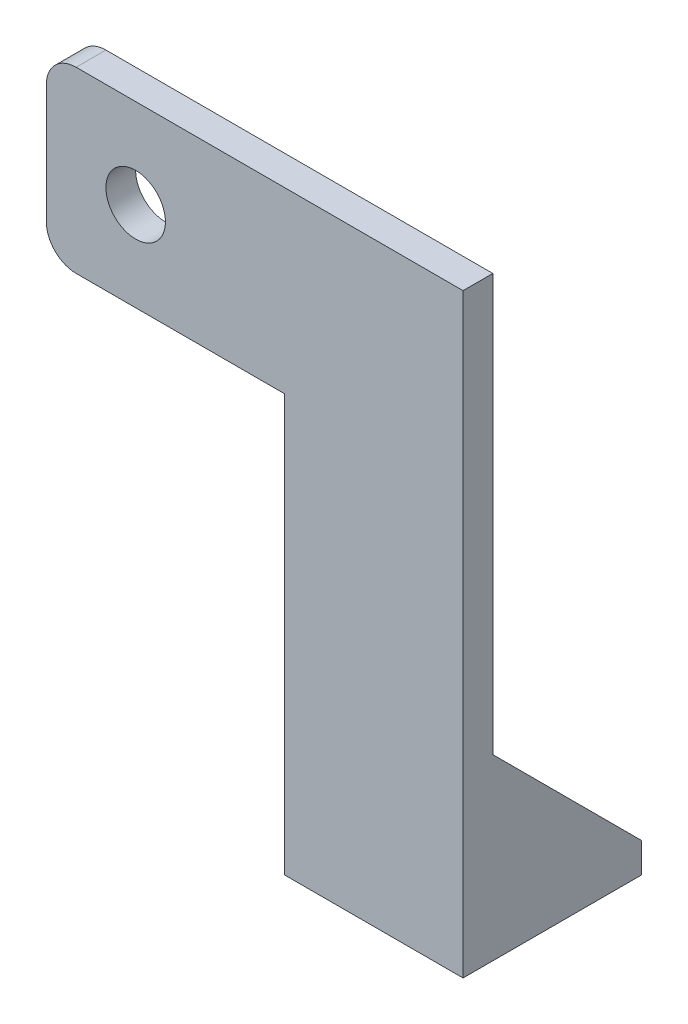
SolidWorks part; units mm, degrees
ref_plane "Front Plane" through (0, 0, 0) normal (0, 0, 1) x (1, 0, 0)
ref_plane "Top Plane" through (0, 0, 0) normal (0, 1, 0) x (1, 0, 0)
ref_plane "Right Plane" through (0, 0, 0) normal (1, 0, 0) x (0, 0, -1)
sketch "Sketch1" plane through (0, 0, 0) normal (0, 0, 1) x (1, 0, 0)
  line L0 (0, -15) -> (6.6093, -15) construction
  line L1 (5, 0) -> (70, 0)
  line L2 (0, -5) -> (0, -25)
  line L3 (5, -30) -> (40, -30)
  line L4 (70, 0) -> (70, -30)
  line L6 (70, -30) -> (70, -95)
  line L7 (70, -95) -> (40, -95)
  line L8 (40, -30) -> (40, -95)
  arc A1 (5, 0) -> (0, -5) centre (5, -5) ccw
  arc A2 (5, -30) -> (0, -25) centre (5, -25) cw
  dimension "D5" = 10
  dimension "D1" = 30
  dimension "D2" = 70
  dimension "D3" = 30
  dimension "D4" = 65
extrude "Boss-Extrude1" add sketch "Sketch1" along normal blind 5 contours L1 L4 L6 L7 L8 L3 A2 L2 A1
ref_plane "Plane1" through (55, 0, 0) normal (-1, 0, 0) x (0, 0, 1)
sketch "Sketch4" plane through (0, 0, 5) normal (0, 0, 1) x (1, 0, 0)
  line L0 (0, -5) -> (0, -25) construction
  line L1 (5, 0) -> (70, 0) construction
  circle A0 centre (15, -15) radius 5
  dimension "D1" = 10
  dimension "D2" = 15
  dimension "D3" = 15
extrude "Cut-Extrude1" cut sketch "Sketch4" against normal blind 5 contours A0
sketch "Sketch5" plane through (0, -95, 0) normal (0, -1, 0) x (1, 0, 0)
  line L0 (70, 5) -> (70, 0) construction
  line L1 (40, 5) -> (70, 5)
  line L2 (40, 5) -> (40, -25)
  line L3 (40, -25) -> (70, -25)
  line L4 (70, 5) -> (70, -25)
  dimension "D1" = 30
extrude "Boss-Extrude4" add sketch "Sketch5" along normal blind 5
sketch "Sketch6" plane through (70, 0, 0) normal (1, 0, 0) x (0, 0, -1)
  line L0 (0, -70) -> (25, -95)
  line L1 (0, 0) -> (0, -95) construction
  line L2 (0, -70) -> (0, -95)
  line L3 (0, -95) -> (25, -95)
extrude "Boss-Extrude5" add sketch "Sketch6" against normal blind 5
mirror "Mirror2" about plane through (55, 0, 0) normal (-1, 0, 0) of "Boss-Extrude5"
